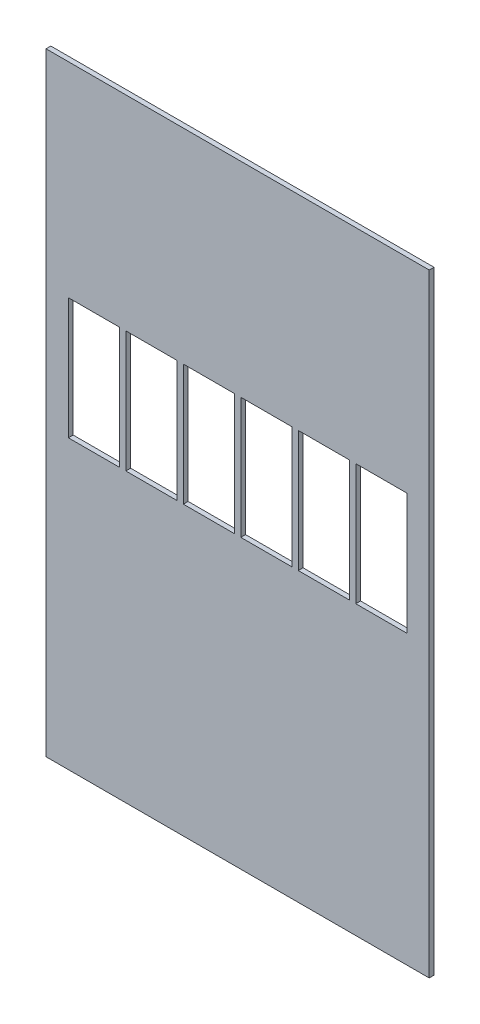
SolidWorks part; units mm, degrees
ref_plane "Front Plane" through (0, 0, 0) normal (0, 0, 1) x (1, 0, 0)
ref_plane "Top Plane" through (0, 0, 0) normal (0, 1, 0) x (1, 0, 0)
ref_plane "Right Plane" through (0, 0, 0) normal (1, 0, 0) x (0, 0, -1)
sketch "Sketch1" plane through (0, 0, 0) normal (0, 0, 1) x (1, 0, 0)
  line L1 (-1371.6, -533.4) -> (1371.6, -533.4)
  line L2 (-1371.6, -533.4) -> (-1371.6, 533.4)
  line L3 (-1371.6, 533.4) -> (1371.6, 533.4)
  line L4 (1371.6, -533.4) -> (1371.6, 533.4)
  point P0 (0, 0)
  dimension "D1" = 2743.2
  dimension "D2" = 1066.8
extrude "Boss-Extrude1" add sketch "Sketch1" along normal blind 38.1
sketch "Sketch2" plane through (0, 0, 38.1) normal (0, 0, 1) x (1, 0, 0)
  line L0 (-1371.6, 533.4) -> (-1371.6, -533.4) construction
  line L1 (-1346.2, 482.6) -> (-939.8, 482.6)
  line L2 (-1346.2, 482.6) -> (-1346.2, -482.6)
  line L3 (-1346.2, -482.6) -> (-939.8, -482.6)
  line L4 (-939.8, 482.6) -> (-939.8, -482.6)
  line L5 (-889, 482.6) -> (-482.6, 482.6)
  line L6 (-889, 482.6) -> (-889, -482.6)
  line L7 (-889, -482.6) -> (-482.6, -482.6)
  line L8 (-482.6, 482.6) -> (-482.6, -482.6)
  line L9 (-431.8, -482.6) -> (-25.4, -482.6)
  line L10 (-431.8, -482.6) -> (-431.8, 482.6)
  line L11 (-431.8, 482.6) -> (-25.4, 482.6)
  line L12 (-25.4, -482.6) -> (-25.4, 482.6)
  line L13 (25.4, -482.6) -> (431.8, -482.6)
  line L14 (25.4, -482.6) -> (25.4, 482.6)
  line L15 (25.4, 482.6) -> (431.8, 482.6)
  line L16 (431.8, -482.6) -> (431.8, 482.6)
  line L17 (482.6, -482.6) -> (889, -482.6)
  line L18 (482.6, -482.6) -> (482.6, 482.6)
  line L19 (482.6, 482.6) -> (889, 482.6)
  line L20 (889, -482.6) -> (889, 482.6)
  line L21 (939.8, -482.6) -> (1346.2, -482.6)
  line L22 (939.8, -482.6) -> (939.8, 482.6)
  line L23 (939.8, 482.6) -> (1346.2, 482.6)
  line L24 (1346.2, -482.6) -> (1346.2, 482.6)
  line L29 (-1371.6, -533.4) -> (1371.6, -533.4) construction
  dimension "D1" = 406.4
  dimension "D2" = 406.4
  dimension "D3" = 406.4
  dimension "D4" = 406.4
  dimension "D5" = 406.4
  dimension "D6" = 406.4
  dimension "D7" = 25.4
  dimension "D8" = 50.8
  dimension "D9" = 50.8
  dimension "D10" = 50.8
  dimension "D11" = 50.8
  dimension "D12" = 50.8
  dimension "D13" = 965.2
  dimension "D14" = 50.8
  dimension "D15" = 965.2
  dimension "D16" = 965.2
  dimension "D17" = 965.2
  dimension "D18" = 965.2
  dimension "D19" = 965.2
extrude "Cut-Extrude1" cut sketch "Sketch2" against normal through all both and the other way through all
sketch "Sketch3" plane through (0, -533.4, 0) normal (0, -1, 0) x (1, 0, 0)
  line L1 (-1371.6, 0) -> (1371.6, 0)
  line L2 (-1371.6, 0) -> (-1371.6, 38.1)
  line L3 (-1371.6, 38.1) -> (1371.6, 38.1)
  line L4 (1371.6, 0) -> (1371.6, 38.1)
extrude "Boss-Extrude2" add sketch "Sketch3" along normal blind 2235.2
sketch "Sketch4" plane through (0, 533.4, 0) normal (0, 1, 0) x (1, 0, 0)
  line L1 (-1371.6, -38.1) -> (1371.6, -38.1)
  line L2 (-1371.6, -38.1) -> (-1371.6, 0)
  line L3 (-1371.6, 0) -> (1371.6, 0)
  line L4 (1371.6, -38.1) -> (1371.6, 0)
extrude "Boss-Extrude3" add sketch "Sketch4" along normal blind 1574.8
sketch "Sketch5" plane through (-1371.6, 0, 0) normal (-1, 0, 0) x (0, 0, 1)
  line L1 (0, 2108.2) -> (38.1, 2108.2)
  line L2 (0, 2108.2) -> (0, -2768.6)
  line L3 (0, -2768.6) -> (38.1, -2768.6)
  line L4 (38.1, 2108.2) -> (38.1, -2768.6)
extrude "Boss-Extrude4" add sketch "Sketch5" along normal blind 152.4
mirror "Mirror1" about plane through (0, 0, 0) normal (1, 0, 0) of "Boss-Extrude4"
